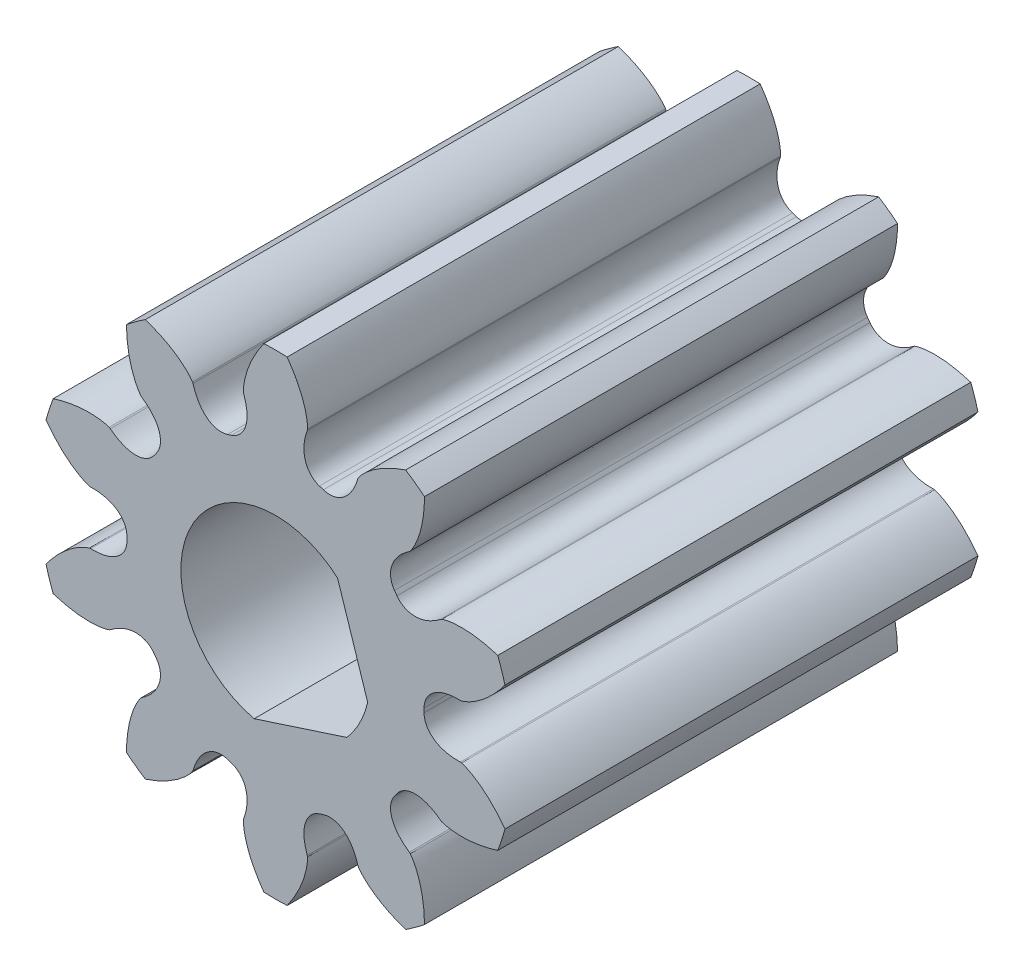
SolidWorks part; units mm, degrees
ref_plane "Front Plane" through (0, 0, 0) normal (0, 0, 1) x (1, 0, 0)
ref_plane "Top Plane" through (0, 0, 0) normal (0, 1, 0) x (1, 0, 0)
ref_plane "Right Plane" through (0, 0, 0) normal (1, 0, 0) x (0, 0, -1)
sketch "Sketch1"
  line L0 (2.4361, 14.0981) -> (2.4176, 14.0011)
  line L1 (0, 19.1675) -> (0, 0) construction
  line L2 (0, 0) -> (0, 19.1675) construction
  line L3 (-2.4361, 14.0981) -> (-2.4176, 14.0011)
  arc A0 (-3.3565, 10.8014) -> (3.3565, 10.8014) centre (0, 0) ccw
  spline S0 degree 3 poles (0, 19.1675) (0.4091, 18.718) (0.9503, 18.0334) (1.5253, 17.0907) (1.8433, 16.4657) (2.08, 15.8962) (2.2459, 15.3905) (2.3525, 14.9558) (2.4222, 14.5338) (2.4407, 14.2555) (2.4361, 14.0981) knots 0 0 0 0 0.317754 0.454552 0.576631 0.68399 0.776631 0.854552 0.917754 1 1 1 1
  spline S1 degree 3 poles (2.4176, 14.0011) (2.3326, 13.767) (2.2324, 13.4128) (2.1686, 12.9356) (2.1589, 12.5901) (2.1905, 12.2478) (2.2716, 11.9071) (2.4153, 11.5697) (2.723, 11.126) (3.0809, 10.8855) (3.3565, 10.8014) knots 0 0 0 0 0.200126 0.294348 0.386168 0.477231 0.569745 0.66645 0.770113 1 1 1 1
  spline S2 degree 3 poles (-2.4176, 14.0011) (-2.3326, 13.767) (-2.2324, 13.4128) (-2.1686, 12.9356) (-2.1589, 12.5901) (-2.1905, 12.2478) (-2.2716, 11.9071) (-2.4153, 11.5697) (-2.723, 11.126) (-3.0809, 10.8855) (-3.3565, 10.8014) knots 0 0 0 0 0.200126 0.294348 0.386168 0.477231 0.569745 0.66645 0.770113 1 1 1 1
  spline S3 degree 3 poles (0, 19.1675) (-0.4091, 18.718) (-0.9503, 18.0334) (-1.5253, 17.0907) (-1.8433, 16.4657) (-2.08, 15.8962) (-2.2459, 15.3905) (-2.3525, 14.9558) (-2.4222, 14.5338) (-2.4407, 14.2555) (-2.4361, 14.0981) knots 0 0 0 0 0.317754 0.454552 0.576631 0.68399 0.776631 0.854552 0.917754 1 1 1 1
  point P2 (0, 19.1675)
  point P4 (0.6151, 18.4382)
  point P5 (1.1227, 17.7322)
  point P6 (1.5306, 17.0614)
  point P7 (1.8474, 16.4366)
  point P8 (2.0828, 15.8672)
  point P9 (2.2476, 15.3617)
  point P10 (2.353, 14.9271)
  point P11 (2.4112, 14.5691)
  point P12 (2.4346, 14.2919)
  point P13 (2.4361, 14.0981)
  point P14 (2.4176, 14.0011)
  point P15 (2.3014, 13.6372)
  point P18 (2.2202, 13.281)
  point P19 (2.1744, 12.9321)
  point P20 (2.1658, 12.5893)
  point P21 (2.1982, 12.2508)
  point P22 (2.2795, 11.915)
  point P23 (2.4224, 11.5834)
  point P24 (2.6443, 11.2662)
  point P25 (2.9589, 10.9909)
  point P26 (3.3565, 10.8014)
  dimension "D1" = 0
  dimension "D2" = 0
  dimension "D3" = 0.6151
  dimension "D4" = 1.1227
  dimension "D24" = 0
other "AlignGroup4" parameters "D1"=14.359, "D2"=4.3343, "D3"=15.4996, "D4"=22.2419, "D5"=1.5306, "D6"=1.8474, "D7"=2.0828, "D8"=2.2476, "D9"=2.353, "D10"=2.4112, "D11"=2.4346, "D12"=2.4361, "D13"=2.4176, "D14"=2.3014, "D15"=2.2202, "D16"=2.1744, "D17"=2.1658, "D18"=2.1982, "D19"=2.2795, "D20"=2.4224, "D21"=2.6443, "D22"=2.9589, "D23"=3.3565, "D24"=0, "D25"=19.1675, "D26"=18.4382, "D27"=17.7322, "D28"=17.0614, "D29"=16.4366, "D30"=15.8672, "D31"=15.3617, "D32"=14.9271, "D33"=14.5691, "D34"=14.2919, "D35"=14.0981, "D36"=14.0011, "D37"=13.6372, "D38"=13.281, "D39"=12.9321, "D40"=12.5893, "D41"=12.2508, "D42"=11.915, "D43"=11.5834, "D44"=11.2662, "D45"=10.9909, "D46"=10.8014
other "AlignGroup5"
extrude "Tooth" add sketch "Sketch1" along normal blind 36
pattern_circular "Teeth" count 10 over 360 about axis through (0, 0, 36) along (0, 0, -1) of "Tooth"
sketch "Sketch6" plane through (0, 0, 0) normal (0, 0, 1) x (1, 0, 0)
  circle A0 centre (0, 0) radius 18.0975
  dimension "D1" = 36.195
extrude "Addendum" cut sketch "Sketch6" along normal through all flip side to cut
sketch "Sketch7" plane through (0, 0, 36) normal (0, 0, 1) x (1, 0, 0)
  line L0 (-1.62, -7.0154) -> (5.4341, -4.7234)
  line L1 (0, 0) -> (3.4953, -10.7573) construction
  line L2 (4.7234, 5.4341) -> (7.0154, -1.62)
  arc A0 (5.4341, -4.7234) -> (7.0154, -1.62) centre (0, 0) ccw
  arc A1 (3.3438, -10.8054) -> (3.6461, -10.7072) centre (0, 0) ccw construction
  arc A2 (4.7234, 5.4341) -> (-1.62, -7.0154) centre (0, 0) ccw
  dimension "D1" = 14.4
  dimension "D2" = 13.3714
  dimension "D3" = 4.1109
  dimension "D4" = 13.3714
extrude "Cut-Extrude4" cut sketch "Sketch7" against normal blind 25
sketch "Sketch8" plane through (1.9071, -5.8694, 0) normal (-0.309, 0.9511, 0) x (0.9511, 0.309, 0)
  line L0 (0, -11) -> (0, -36) construction
  line L4 (-3.7086, -36) -> (3.7086, -36)
  line L5 (3.7086, -36) -> (3.7086, -11)
  line L6 (3.7086, -11) -> (-3.7086, -11)
  line L7 (-3.7086, -11) -> (-3.7086, -36)
  line L8 (-3.7086, -36) -> (3.7086, -36) construction
  line L9 (3.7086, -36) -> (3.7086, -11) construction
  line L10 (3.7086, -11) -> (-3.7086, -11) construction
  line L11 (-3.7086, -11) -> (-3.7086, -36) construction
  circle A0 centre (0, -23.5) radius 1.5
  point P10 (0, -23.5)
  dimension "D2" = 3
  dimension "D1" = 0
extrude "Cut-Extrude5" cut sketch "Sketch8" against normal through all
sketch "Sketch9" plane through (0, 0, 0) normal (0, 0, -1) x (-1, 0, 0)
  line L20 (14.1609, -2.0397) -> (14.0629, -2.0273)
  line L21 (14.0629, 2.0273) -> (14.1609, 2.0397)
  line L22 (12.6553, 6.6734) -> (12.5688, 6.6258)
  line L23 (10.1855, 9.9061) -> (10.2575, 9.9737)
  line L24 (6.3158, 12.8375) -> (6.2738, 12.7481)
  line L25 (2.4176, 14.0011) -> (2.4361, 14.0981)
  line L26 (-2.4361, 14.0981) -> (-2.4176, 14.0011)
  line L27 (-6.2738, 12.7481) -> (-6.3158, 12.8375)
  line L28 (-10.2575, 9.9737) -> (-10.1855, 9.9061)
  line L29 (-12.5688, 6.6258) -> (-12.6553, 6.6734)
  line L30 (-14.1609, 2.0397) -> (-14.0629, 2.0273)
  line L31 (-14.0629, -2.0273) -> (-14.1609, -2.0397)
  line L32 (-12.6553, -6.6734) -> (-12.5688, -6.6258)
  line L33 (-10.1855, -9.9061) -> (-10.2575, -9.9737)
  line L34 (-6.3158, -12.8375) -> (-6.2738, -12.7481)
  line L35 (-2.4176, -14.0011) -> (-2.4361, -14.0981)
  line L36 (2.4361, -14.0981) -> (2.4176, -14.0011)
  line L37 (6.2738, -12.7481) -> (6.3158, -12.8375)
  line L38 (10.2575, -9.9737) -> (10.1855, -9.9061)
  line L39 (12.5688, -6.6258) -> (12.6553, -6.6734)
  line L40 (14.1609, -2.0397) -> (14.0629, -2.0273)
  line L41 (14.0629, 2.0273) -> (14.1609, 2.0397)
  line L42 (12.6553, 6.6734) -> (12.5688, 6.6258)
  line L43 (10.1855, 9.9061) -> (10.2575, 9.9737)
  line L44 (6.3158, 12.8375) -> (6.2738, 12.7481)
  line L45 (2.4176, 14.0011) -> (2.4361, 14.0981)
  line L46 (-2.4361, 14.0981) -> (-2.4176, 14.0011)
  line L47 (-6.2738, 12.7481) -> (-6.3158, 12.8375)
  line L48 (-10.2575, 9.9737) -> (-10.1855, 9.9061)
  line L49 (-12.5688, 6.6258) -> (-12.6553, 6.6734)
  line L50 (-14.1609, 2.0397) -> (-14.0629, 2.0273)
  line L51 (-14.0629, -2.0273) -> (-14.1609, -2.0397)
  line L52 (-12.6553, -6.6734) -> (-12.5688, -6.6258)
  line L53 (-10.1855, -9.9061) -> (-10.2575, -9.9737)
  line L54 (-6.3158, -12.8375) -> (-6.2738, -12.7481)
  line L55 (-2.4176, -14.0011) -> (-2.4361, -14.0981)
  line L56 (2.4361, -14.0981) -> (2.4176, -14.0011)
  line L57 (6.2738, -12.7481) -> (6.3158, -12.8375)
  line L58 (10.2575, -9.9737) -> (10.1855, -9.9061)
  line L59 (12.5688, -6.6258) -> (12.6553, -6.6734)
  arc A20 (16.9173, -6.4284) -> (17.4649, -4.7431) centre (0, 0) ccw
  arc A21 (11.3098, -0.1589) -> (11.3098, 0.1589) centre (0, 0) ccw
  arc A22 (17.4649, 4.7431) -> (16.9173, 6.4284) centre (0, 0) ccw
  arc A23 (9.2433, 6.5192) -> (9.0564, 6.7763) centre (0, 0) ccw
  arc A24 (11.3415, 14.1028) -> (9.9079, 15.1444) centre (0, 0) ccw
  arc A25 (3.6461, 10.7072) -> (3.3438, 10.8054) centre (0, 0) ccw
  arc A26 (0.886, 18.0758) -> (-0.886, 18.0758) centre (0, 0) ccw
  arc A27 (-3.3438, 10.8054) -> (-3.6461, 10.7072) centre (0, 0) ccw
  arc A28 (-9.9079, 15.1444) -> (-11.3415, 14.1028) centre (0, 0) ccw
  arc A29 (-9.0564, 6.7763) -> (-9.2433, 6.5192) centre (0, 0) ccw
  arc A30 (-16.9173, 6.4284) -> (-17.4649, 4.7431) centre (0, 0) ccw
  arc A31 (-11.3098, 0.1589) -> (-11.3098, -0.1589) centre (0, 0) ccw
  arc A32 (-17.4649, -4.7431) -> (-16.9173, -6.4284) centre (0, 0) ccw
  arc A33 (-9.2433, -6.5192) -> (-9.0564, -6.7763) centre (0, 0) ccw
  arc A34 (-11.3415, -14.1028) -> (-9.9079, -15.1444) centre (0, 0) ccw
  arc A35 (-3.6461, -10.7072) -> (-3.3438, -10.8054) centre (0, 0) ccw
  arc A36 (-0.886, -18.0758) -> (0.886, -18.0758) centre (0, 0) ccw
  arc A37 (3.3438, -10.8054) -> (3.6461, -10.7072) centre (0, 0) ccw
  arc A38 (9.9079, -15.1444) -> (11.3415, -14.1028) centre (0, 0) ccw
  arc A39 (9.0564, -6.7763) -> (9.2433, -6.5192) centre (0, 0) ccw
  arc A40 (16.9173, -6.4284) -> (17.4649, -4.7431) centre (0, 0) ccw
  arc A41 (11.3098, -0.1589) -> (11.3098, 0.1589) centre (0, 0) ccw
  arc A42 (17.4649, 4.7431) -> (16.9173, 6.4284) centre (0, 0) ccw
  arc A43 (9.2433, 6.5192) -> (9.0564, 6.7763) centre (0, 0) ccw
  arc A44 (11.3415, 14.1028) -> (9.9079, 15.1444) centre (0, 0) ccw
  arc A45 (3.6461, 10.7072) -> (3.3438, 10.8054) centre (0, 0) ccw
  arc A46 (0.886, 18.0758) -> (-0.886, 18.0758) centre (0, 0) ccw
  arc A47 (-3.3438, 10.8054) -> (-3.6461, 10.7072) centre (0, 0) ccw
  arc A48 (-9.9079, 15.1444) -> (-11.3415, 14.1028) centre (0, 0) ccw
  arc A49 (-9.0564, 6.7763) -> (-9.2433, 6.5192) centre (0, 0) ccw
  arc A50 (-16.9173, 6.4284) -> (-17.4649, 4.7431) centre (0, 0) ccw
  arc A51 (-11.3098, 0.1589) -> (-11.3098, -0.1589) centre (0, 0) ccw
  arc A52 (-17.4649, -4.7431) -> (-16.9173, -6.4284) centre (0, 0) ccw
  arc A53 (-9.2433, -6.5192) -> (-9.0564, -6.7763) centre (0, 0) ccw
  arc A54 (-11.3415, -14.1028) -> (-9.9079, -15.1444) centre (0, 0) ccw
  arc A55 (-3.6461, -10.7072) -> (-3.3438, -10.8054) centre (0, 0) ccw
  arc A56 (-0.886, -18.0758) -> (0.886, -18.0758) centre (0, 0) ccw
  arc A57 (3.3438, -10.8054) -> (3.6461, -10.7072) centre (0, 0) ccw
  arc A58 (9.9079, -15.1444) -> (11.3415, -14.1028) centre (0, 0) ccw
  arc A59 (9.0564, -6.7763) -> (9.2433, -6.5192) centre (0, 0) ccw
  spline S40 degree 3 poles (522.5428, 2951.3914) (-112.6678, -210.8006) (43.5083, -35.0589) (16.7256, -3.8307) (16.2294, -3.3351) (15.7609, -2.934) (15.3313, -2.62) (14.9507, -2.3842) (4.0763, 3.2477) (-28.6818, -37.3785) (-500.9762, -2956.8331) knots -21.152861 -21.152861 -21.152861 -21.152861 0.07269 0.209488 0.331567 0.438926 0.531567 0.609488 0.67269 6.927682 6.927682 6.927682 6.927682 only from (17.4649, -4.7431) to (14.1609, -2.0397)
  spline S41 degree 3 poles (-1882.5898, -2326.0124) (70.5572, 137.468) (32.2563, -5.4661) (12.9726, -1.9349) (12.641, -1.8374) (12.3253, -1.7014) (12.0263, -1.519) (11.7499, -1.2781) (4.3858, 8.4005) (109.0954, 85.4158) (1889.5302, -2336.0275) knots -15.333647 -15.333647 -15.333647 -15.333647 0.20368 0.297902 0.389722 0.480785 0.573299 0.670004 0.773667 10.262957 10.262957 10.262957 10.262957 only from (14.0629, -2.0273) to (11.3098, -0.1589)
  spline S42 degree 3 poles (1889.5208, 2336.0147) (109.095, -85.4156) (4.3859, -8.4005) (11.7499, 1.2781) (12.0263, 1.519) (12.3253, 1.7014) (12.641, 1.8374) (12.9726, 1.9349) (32.2563, 5.4662) (70.5573, -137.4686) (-1882.6014, 2326.027) knots -9.26294 -9.26294 -9.26294 -9.26294 0.226333 0.329996 0.426701 0.519215 0.610278 0.702098 0.79632 16.333677 16.333677 16.333677 16.333677 only from (11.3098, 0.1589) to (14.0629, 2.0273)
  spline S43 degree 3 poles (-500.9951, 2956.9497) (-28.6827, 37.3796) (4.0761, -3.2478) (14.9507, 2.3842) (15.3313, 2.62) (15.7609, 2.934) (16.2294, 3.3351) (16.7256, 3.8307) (43.5082, 35.0587) (-112.6664, 210.799) (522.5344, -2951.3495) knots -5.927765 -5.927765 -5.927765 -5.927765 0.32731 0.390512 0.468433 0.561074 0.668433 0.790512 0.92731 22.152768 22.152768 22.152768 22.152768 only from (14.1609, 2.0397) to (17.4649, 4.7431)
  spline S44 degree 3 poles (-1312.0383, 2694.8688) (32.7553, -236.7657) (55.8061, -2.7897) (15.7829, 6.7319) (15.0902, 6.8413) (14.4754, 6.8904) (13.9432, 6.8919) (13.4968, 6.8589) (1.3888, 5.0234) (-1.2335, -47.0986) (1332.6846, -2686.5947) knots -21.152861 -21.152861 -21.152861 -21.152861 0.07269 0.209488 0.331567 0.438926 0.531567 0.609488 0.67269 6.927682 6.927682 6.927682 6.927682 only from (16.9173, 6.4284) to (12.6553, 6.6734)
  spline S45 degree 3 poles (-155.8514, -2988.342) (-23.7197, 152.6864) (29.3088, 14.5375) (11.6324, 6.0598) (11.3068, 5.9437) (10.9714, 5.8681) (10.6223, 5.8399) (10.2571, 5.8724) (-1.3895, 9.3741) (38.0539, 133.2275) (2901.7445, -779.248) knots -15.333647 -15.333647 -15.333647 -15.333647 0.20368 0.297902 0.389722 0.480785 0.573299 0.670004 0.773667 10.262957 10.262957 10.262957 10.262957 only from (12.5688, 6.6258) to (9.2433, 6.5192)
  spline S46 degree 3 poles (155.5794, 3000.508) (138.4657, -4.9782) (8.4859, -4.2182) (8.7546, 7.9404) (8.8366, 8.2978) (8.9713, 8.6211) (9.1468, 8.9167) (9.3578, 9.1905) (22.883, 23.382) (137.8841, -69.7418) (-2890.2609, 775.23) knots -9.26294 -9.26294 -9.26294 -9.26294 0.226333 0.329996 0.426701 0.519215 0.610278 0.702098 0.79632 16.333677 16.333677 16.333677 16.333677 only from (9.0564, 6.7763) to (10.1855, 9.9061)
  spline S47 degree 3 poles (-2143.365, 2097.745) (-45.1759, 13.3815) (5.2067, -0.2316) (10.694, 10.7167) (10.8633, 11.1311) (11.0263, 11.6377) (11.1696, 12.2376) (11.2796, 12.9301) (14.5919, 53.9366) (-215.0536, 104.3164) (2157.4989, -2080.5539) knots -5.927765 -5.927765 -5.927765 -5.927765 0.32731 0.390512 0.468433 0.561074 0.668433 0.790512 0.92731 22.152768 22.152768 22.152768 22.152768 only from (10.2575, 9.9737) to (11.3415, 14.1028)
  spline S48 degree 3 poles (-2645.4654, 1408.9979) (165.667, -172.2944) (46.7878, 30.5451) (8.8117, 14.7232) (8.187, 14.4045) (7.6608, 14.0829) (7.2294, 13.7713) (6.8876, 13.4822) (-1.8291, 4.8804) (26.6859, -38.8286) (2657.3052, -1390.1684) knots -21.152861 -21.152861 -21.152861 -21.152861 0.07269 0.209488 0.331567 0.438926 0.531567 0.609488 0.67269 6.927682 6.927682 6.927682 6.927682 only from (9.9079, 15.1444) to (6.3158, 12.8375)
  spline S49 degree 3 poles (1630.417, -2509.2266) (-108.9365, 109.5838) (15.1663, 28.9884) (5.849, 11.7398) (5.6537, 11.4545) (5.4269, 11.1962) (5.161, 10.9682) (4.8465, 10.7798) (-6.6341, 6.7671) (-47.523, 130.1508) (2805.5911, 1075.1778) knots -15.333647 -15.333647 -15.333647 -15.333647 0.20368 0.297902 0.389722 0.480785 0.573299 0.670004 0.773667 10.262957 10.262957 10.262957 10.262957 only from (6.2738, 12.7481) to (3.6461, 10.7072)
  spline S50 degree 3 poles (-1637.788, 2518.9093) (114.9472, 77.3607) (9.3447, 1.5753) (2.4153, 11.5697) (2.2716, 11.9071) (2.1905, 12.2478) (2.1589, 12.5901) (2.1686, 12.9356) (4.7691, 32.3667) (152.5438, 24.6239) (-2793.939, -1071.6785) knots -9.26294 -9.26294 -9.26294 -9.26294 0.226333 0.329996 0.426701 0.519215 0.610278 0.702098 0.79632 16.333677 16.333677 16.333677 16.333677 only from (3.3438, 10.8054) to (2.4176, 14.0011)
  spline S51 degree 3 poles (-2967.0423, 437.2731) (-44.4135, -15.7279) (4.3484, 2.873) (2.3525, 14.9558) (2.2459, 15.3905) (2.08, 15.8962) (1.8433, 16.4657) (1.5253, 17.0907) (-19.8981, 52.2125) (-235.2976, -42.0116) (2968.3722, -415.0574) knots -5.927765 -5.927765 -5.927765 -5.927765 0.32731 0.390512 0.468433 0.561074 0.668433 0.790512 0.92731 22.152768 22.152768 22.152768 22.152768 only from (2.4361, 14.0981) to (0.886, 18.0758)
  spline S52 degree 3 poles (-2968.4147, -415.0623) (235.2995, -42.0125) (19.8981, 52.2127) (-1.5253, 17.0907) (-1.8433, 16.4657) (-2.08, 15.8962) (-2.2459, 15.3905) (-2.3525, 14.9558) (-4.3484, 2.8732) (44.4122, -15.7274) (2966.9256, 437.255) knots -21.152861 -21.152861 -21.152861 -21.152861 0.07269 0.209488 0.331567 0.438926 0.531567 0.609488 0.67269 6.927682 6.927682 6.927682 6.927682 only from (-0.886, 18.0758) to (-2.4361, 14.0981)
  spline S53 degree 3 poles (2793.9215, -1071.6719) (-152.5432, 24.6239) (-4.7691, 32.3667) (-2.1686, 12.9356) (-2.1589, 12.5901) (-2.1905, 12.2478) (-2.2716, 11.9071) (-2.4153, 11.5697) (-9.3447, 1.5753) (-114.9476, 77.3609) (1637.7972, 2518.9222) knots -15.333647 -15.333647 -15.333647 -15.333647 0.20368 0.297902 0.389722 0.480785 0.573299 0.670004 0.773667 10.262957 10.262957 10.262957 10.262957 only from (-2.4176, 14.0011) to (-3.3438, 10.8054)
  spline S54 degree 3 poles (-2805.576, 1075.1728) (47.5228, 130.1504) (6.6341, 6.7671) (-4.8465, 10.7798) (-5.161, 10.9682) (-5.4269, 11.1962) (-5.6537, 11.4545) (-5.849, 11.7398) (-15.1664, 28.9884) (108.937, 109.5841) (-1630.4273, -2509.2422) knots -9.26294 -9.26294 -9.26294 -9.26294 0.226333 0.329996 0.426701 0.519215 0.610278 0.702098 0.79632 16.333677 16.333677 16.333677 16.333677 only from (-3.6461, 10.7072) to (-6.2738, 12.7481)
  spline S55 degree 3 poles (-2657.4103, -1390.2224) (-26.6867, -38.8298) (1.8292, 4.8803) (-6.8876, 13.4822) (-7.2294, 13.7713) (-7.6608, 14.0829) (-8.187, 14.4045) (-8.8117, 14.7232) (-46.7876, 30.545) (-165.666, -172.2926) (2645.4282, 1408.9769) knots -5.927765 -5.927765 -5.927765 -5.927765 0.32731 0.390512 0.468433 0.561074 0.668433 0.790512 0.92731 22.152768 22.152768 22.152768 22.152768 only from (-6.3158, 12.8375) to (-9.9079, 15.1444)
  spline S56 degree 3 poles (-2157.5304, -2080.5828) (215.0556, 104.3168) (-14.5919, 53.9368) (-11.2796, 12.9301) (-11.1696, 12.2376) (-11.0263, 11.6377) (-10.8633, 11.1311) (-10.694, 10.7167) (-5.2067, -0.2315) (45.1746, 13.3811) (2143.2812, 2097.6618) knots -21.152861 -21.152861 -21.152861 -21.152861 0.07269 0.209488 0.331567 0.438926 0.531567 0.609488 0.67269 6.927682 6.927682 6.927682 6.927682 only from (-11.3415, 14.1028) to (-10.2575, 9.9737)
  spline S57 degree 3 poles (2890.2429, 775.225) (-137.8836, -69.7415) (-22.8829, 23.382) (-9.3578, 9.1905) (-9.1468, 8.9167) (-8.9713, 8.6211) (-8.8366, 8.2978) (-8.7546, 7.9404) (-8.4859, -4.2182) (-138.4662, -4.9782) (-155.5795, 3000.5239) knots -15.333647 -15.333647 -15.333647 -15.333647 0.20368 0.297902 0.389722 0.480785 0.573299 0.670004 0.773667 10.262957 10.262957 10.262957 10.262957 only from (-10.1855, 9.9061) to (-9.0564, 6.7763)
  spline S58 degree 3 poles (-2901.7294, -779.2431) (-38.0537, 133.2271) (1.3895, 9.3741) (-10.2571, 5.8724) (-10.6223, 5.8399) (-10.9714, 5.8681) (-11.3068, 5.9437) (-11.6324, 6.0598) (-29.3088, 14.5376) (23.7199, 152.687) (155.8522, -2988.3608) knots -9.26294 -9.26294 -9.26294 -9.26294 0.226333 0.329996 0.426701 0.519215 0.610278 0.702098 0.79632 16.333677 16.333677 16.333677 16.333677 only from (-9.2433, 6.5192) to (-12.5688, 6.6258)
  spline S59 degree 3 poles (-1332.7379, -2686.7001) (1.2336, -47.1) (-1.3887, 5.0234) (-13.4968, 6.8589) (-13.9432, 6.8919) (-14.4754, 6.8904) (-15.0902, 6.8413) (-15.7829, 6.7319) (-55.8059, -2.7896) (-32.7555, -236.7637) (1312.0205, 2694.8299) knots -5.927765 -5.927765 -5.927765 -5.927765 0.32731 0.390512 0.468433 0.561074 0.668433 0.790512 0.92731 22.152768 22.152768 22.152768 22.152768 only from (-12.6553, 6.6734) to (-16.9173, 6.4284)
  spline S60 degree 3 poles (-522.5428, -2951.3914) (112.6678, 210.8006) (-43.5083, 35.0589) (-16.7256, 3.8307) (-16.2294, 3.3351) (-15.7609, 2.934) (-15.3313, 2.62) (-14.9507, 2.3842) (-4.0763, -3.2477) (28.6818, 37.3785) (500.9762, 2956.8331) knots -21.152861 -21.152861 -21.152861 -21.152861 0.07269 0.209488 0.331567 0.438926 0.531567 0.609488 0.67269 6.927682 6.927682 6.927682 6.927682 only from (-17.4649, 4.7431) to (-14.1609, 2.0397)
  spline S61 degree 3 poles (1882.5898, 2326.0124) (-70.5572, -137.468) (-32.2563, 5.4661) (-12.9726, 1.9349) (-12.641, 1.8374) (-12.3253, 1.7014) (-12.0263, 1.519) (-11.7499, 1.2781) (-4.3858, -8.4005) (-109.0954, -85.4158) (-1889.5302, 2336.0275) knots -15.333647 -15.333647 -15.333647 -15.333647 0.20368 0.297902 0.389722 0.480785 0.573299 0.670004 0.773667 10.262957 10.262957 10.262957 10.262957 only from (-14.0629, 2.0273) to (-11.3098, 0.1589)
  spline S62 degree 3 poles (-1889.5208, -2336.0147) (-109.095, 85.4156) (-4.3859, 8.4005) (-11.7499, -1.2781) (-12.0263, -1.519) (-12.3253, -1.7014) (-12.641, -1.8374) (-12.9726, -1.9349) (-32.2563, -5.4662) (-70.5573, 137.4686) (1882.6014, -2326.027) knots -9.26294 -9.26294 -9.26294 -9.26294 0.226333 0.329996 0.426701 0.519215 0.610278 0.702098 0.79632 16.333677 16.333677 16.333677 16.333677 only from (-11.3098, -0.1589) to (-14.0629, -2.0273)
  spline S63 degree 3 poles (500.9951, -2956.9497) (28.6827, -37.3796) (-4.0761, 3.2478) (-14.9507, -2.3842) (-15.3313, -2.62) (-15.7609, -2.934) (-16.2294, -3.3351) (-16.7256, -3.8307) (-43.5082, -35.0587) (112.6664, -210.799) (-522.5344, 2951.3495) knots -5.927765 -5.927765 -5.927765 -5.927765 0.32731 0.390512 0.468433 0.561074 0.668433 0.790512 0.92731 22.152768 22.152768 22.152768 22.152768 only from (-14.1609, -2.0397) to (-17.4649, -4.7431)
  spline S64 degree 3 poles (1312.0383, -2694.8688) (-32.7553, 236.7657) (-55.8061, 2.7897) (-15.7829, -6.7319) (-15.0902, -6.8413) (-14.4754, -6.8904) (-13.9432, -6.8919) (-13.4968, -6.8589) (-1.3888, -5.0234) (1.2335, 47.0986) (-1332.6846, 2686.5947) knots -21.152861 -21.152861 -21.152861 -21.152861 0.07269 0.209488 0.331567 0.438926 0.531567 0.609488 0.67269 6.927682 6.927682 6.927682 6.927682 only from (-16.9173, -6.4284) to (-12.6553, -6.6734)
  spline S65 degree 3 poles (155.8514, 2988.342) (23.7197, -152.6864) (-29.3088, -14.5375) (-11.6324, -6.0598) (-11.3068, -5.9437) (-10.9714, -5.8681) (-10.6223, -5.8399) (-10.2571, -5.8724) (1.3895, -9.3741) (-38.0539, -133.2275) (-2901.7445, 779.248) knots -15.333647 -15.333647 -15.333647 -15.333647 0.20368 0.297902 0.389722 0.480785 0.573299 0.670004 0.773667 10.262957 10.262957 10.262957 10.262957 only from (-12.5688, -6.6258) to (-9.2433, -6.5192)
  spline S66 degree 3 poles (-155.5794, -3000.508) (-138.4657, 4.9782) (-8.4859, 4.2182) (-8.7546, -7.9404) (-8.8366, -8.2978) (-8.9713, -8.6211) (-9.1468, -8.9167) (-9.3578, -9.1905) (-22.883, -23.382) (-137.8841, 69.7418) (2890.2609, -775.23) knots -9.26294 -9.26294 -9.26294 -9.26294 0.226333 0.329996 0.426701 0.519215 0.610278 0.702098 0.79632 16.333677 16.333677 16.333677 16.333677 only from (-9.0564, -6.7763) to (-10.1855, -9.9061)
  spline S67 degree 3 poles (2143.365, -2097.745) (45.1759, -13.3815) (-5.2067, 0.2316) (-10.694, -10.7167) (-10.8633, -11.1311) (-11.0263, -11.6377) (-11.1696, -12.2376) (-11.2796, -12.9301) (-14.5919, -53.9366) (215.0536, -104.3164) (-2157.4989, 2080.5539) knots -5.927765 -5.927765 -5.927765 -5.927765 0.32731 0.390512 0.468433 0.561074 0.668433 0.790512 0.92731 22.152768 22.152768 22.152768 22.152768 only from (-10.2575, -9.9737) to (-11.3415, -14.1028)
  spline S68 degree 3 poles (2645.4654, -1408.9979) (-165.667, 172.2944) (-46.7878, -30.5451) (-8.8117, -14.7232) (-8.187, -14.4045) (-7.6608, -14.0829) (-7.2294, -13.7713) (-6.8876, -13.4822) (1.8291, -4.8804) (-26.6859, 38.8286) (-2657.3052, 1390.1684) knots -21.152861 -21.152861 -21.152861 -21.152861 0.07269 0.209488 0.331567 0.438926 0.531567 0.609488 0.67269 6.927682 6.927682 6.927682 6.927682 only from (-9.9079, -15.1444) to (-6.3158, -12.8375)
  spline S69 degree 3 poles (-1630.417, 2509.2266) (108.9365, -109.5838) (-15.1663, -28.9884) (-5.849, -11.7398) (-5.6537, -11.4545) (-5.4269, -11.1962) (-5.161, -10.9682) (-4.8465, -10.7798) (6.6341, -6.7671) (47.523, -130.1508) (-2805.5911, -1075.1778) knots -15.333647 -15.333647 -15.333647 -15.333647 0.20368 0.297902 0.389722 0.480785 0.573299 0.670004 0.773667 10.262957 10.262957 10.262957 10.262957 only from (-6.2738, -12.7481) to (-3.6461, -10.7072)
  spline S70 degree 3 poles (1637.788, -2518.9093) (-114.9472, -77.3607) (-9.3447, -1.5753) (-2.4153, -11.5697) (-2.2716, -11.9071) (-2.1905, -12.2478) (-2.1589, -12.5901) (-2.1686, -12.9356) (-4.7691, -32.3667) (-152.5438, -24.6239) (2793.939, 1071.6785) knots -9.26294 -9.26294 -9.26294 -9.26294 0.226333 0.329996 0.426701 0.519215 0.610278 0.702098 0.79632 16.333677 16.333677 16.333677 16.333677 only from (-3.3438, -10.8054) to (-2.4176, -14.0011)
  spline S71 degree 3 poles (2967.0423, -437.2731) (44.4135, 15.7279) (-4.3484, -2.873) (-2.3525, -14.9558) (-2.2459, -15.3905) (-2.08, -15.8962) (-1.8433, -16.4657) (-1.5253, -17.0907) (19.8981, -52.2125) (235.2976, 42.0116) (-2968.3722, 415.0574) knots -5.927765 -5.927765 -5.927765 -5.927765 0.32731 0.390512 0.468433 0.561074 0.668433 0.790512 0.92731 22.152768 22.152768 22.152768 22.152768 only from (-2.4361, -14.0981) to (-0.886, -18.0758)
  spline S72 degree 3 poles (2968.4147, 415.0623) (-235.2995, 42.0125) (-19.8981, -52.2127) (1.5253, -17.0907) (1.8433, -16.4657) (2.08, -15.8962) (2.2459, -15.3905) (2.3525, -14.9558) (4.3484, -2.8732) (-44.4122, 15.7274) (-2966.9256, -437.255) knots -21.152861 -21.152861 -21.152861 -21.152861 0.07269 0.209488 0.331567 0.438926 0.531567 0.609488 0.67269 6.927682 6.927682 6.927682 6.927682 only from (0.886, -18.0758) to (2.4361, -14.0981)
  spline S73 degree 3 poles (-2793.9215, 1071.6719) (152.5432, -24.6239) (4.7691, -32.3667) (2.1686, -12.9356) (2.1589, -12.5901) (2.1905, -12.2478) (2.2716, -11.9071) (2.4153, -11.5697) (9.3447, -1.5753) (114.9476, -77.3609) (-1637.7972, -2518.9222) knots -15.333647 -15.333647 -15.333647 -15.333647 0.20368 0.297902 0.389722 0.480785 0.573299 0.670004 0.773667 10.262957 10.262957 10.262957 10.262957 only from (2.4176, -14.0011) to (3.3438, -10.8054)
  spline S74 degree 3 poles (2805.576, -1075.1728) (-47.5228, -130.1504) (-6.6341, -6.7671) (4.8465, -10.7798) (5.161, -10.9682) (5.4269, -11.1962) (5.6537, -11.4545) (5.849, -11.7398) (15.1664, -28.9884) (-108.937, -109.5841) (1630.4273, 2509.2422) knots -9.26294 -9.26294 -9.26294 -9.26294 0.226333 0.329996 0.426701 0.519215 0.610278 0.702098 0.79632 16.333677 16.333677 16.333677 16.333677 only from (3.6461, -10.7072) to (6.2738, -12.7481)
  spline S75 degree 3 poles (2657.4103, 1390.2224) (26.6867, 38.8298) (-1.8292, -4.8803) (6.8876, -13.4822) (7.2294, -13.7713) (7.6608, -14.0829) (8.187, -14.4045) (8.8117, -14.7232) (46.7876, -30.545) (165.666, 172.2926) (-2645.4282, -1408.9769) knots -5.927765 -5.927765 -5.927765 -5.927765 0.32731 0.390512 0.468433 0.561074 0.668433 0.790512 0.92731 22.152768 22.152768 22.152768 22.152768 only from (6.3158, -12.8375) to (9.9079, -15.1444)
  spline S76 degree 3 poles (2157.5304, 2080.5828) (-215.0556, -104.3168) (14.5919, -53.9368) (11.2796, -12.9301) (11.1696, -12.2376) (11.0263, -11.6377) (10.8633, -11.1311) (10.694, -10.7167) (5.2067, 0.2315) (-45.1746, -13.3811) (-2143.2812, -2097.6618) knots -21.152861 -21.152861 -21.152861 -21.152861 0.07269 0.209488 0.331567 0.438926 0.531567 0.609488 0.67269 6.927682 6.927682 6.927682 6.927682 only from (11.3415, -14.1028) to (10.2575, -9.9737)
  spline S77 degree 3 poles (-2890.2429, -775.225) (137.8836, 69.7415) (22.8829, -23.382) (9.3578, -9.1905) (9.1468, -8.9167) (8.9713, -8.6211) (8.8366, -8.2978) (8.7546, -7.9404) (8.4859, 4.2182) (138.4662, 4.9782) (155.5795, -3000.5239) knots -15.333647 -15.333647 -15.333647 -15.333647 0.20368 0.297902 0.389722 0.480785 0.573299 0.670004 0.773667 10.262957 10.262957 10.262957 10.262957 only from (10.1855, -9.9061) to (9.0564, -6.7763)
  spline S78 degree 3 poles (2901.7294, 779.2431) (38.0537, -133.2271) (-1.3895, -9.3741) (10.2571, -5.8724) (10.6223, -5.8399) (10.9714, -5.8681) (11.3068, -5.9437) (11.6324, -6.0598) (29.3088, -14.5376) (-23.7199, -152.687) (-155.8522, 2988.3608) knots -9.26294 -9.26294 -9.26294 -9.26294 0.226333 0.329996 0.426701 0.519215 0.610278 0.702098 0.79632 16.333677 16.333677 16.333677 16.333677 only from (9.2433, -6.5192) to (12.5688, -6.6258)
  spline S79 degree 3 poles (1332.7379, 2686.7001) (-1.2336, 47.1) (1.3887, -5.0234) (13.4968, -6.8589) (13.9432, -6.8919) (14.4754, -6.8904) (15.0902, -6.8413) (15.7829, -6.7319) (55.8059, 2.7896) (32.7555, 236.7637) (-1312.0205, -2694.8299) knots -5.927765 -5.927765 -5.927765 -5.927765 0.32731 0.390512 0.468433 0.561074 0.668433 0.790512 0.92731 22.152768 22.152768 22.152768 22.152768 only from (12.6553, -6.6734) to (16.9173, -6.4284)
  spline S80 degree 3 poles (17.4649, -4.7431) (17.3825, -4.6311) (17.1389, -4.3127) (16.7256, -3.8307) (16.2294, -3.3351) (15.7609, -2.934) (15.3313, -2.62) (14.9507, -2.3842) (14.571, -2.1876) (14.312, -2.084) (14.1609, -2.0397) knots 0 0 0 0 0.07269 0.209488 0.331567 0.438926 0.531567 0.609488 0.67269 0.754936 0.754936 0.754936 0.754936
  spline S81 degree 3 poles (14.0629, -2.0273) (13.814, -2.0358) (13.4462, -2.0216) (12.9726, -1.9349) (12.641, -1.8374) (12.3253, -1.7014) (12.0263, -1.519) (11.7499, -1.2781) (11.4256, -0.8519) (11.3073, -0.4425) (11.3098, -0.1589) knots 0.003554 0.003554 0.003554 0.003554 0.20368 0.297902 0.389722 0.480785 0.573299 0.670004 0.773667 1 1 1 1
  spline S82 degree 3 poles (11.3098, 0.1589) (11.3073, 0.4425) (11.4256, 0.8519) (11.7499, 1.2781) (12.0263, 1.519) (12.3253, 1.7014) (12.641, 1.8374) (12.9726, 1.9349) (13.4462, 2.0216) (13.814, 2.0358) (14.0629, 2.0273) knots 0 0 0 0 0.226333 0.329996 0.426701 0.519215 0.610278 0.702098 0.79632 0.996446 0.996446 0.996446 0.996446
  spline S83 degree 3 poles (14.1609, 2.0397) (14.312, 2.084) (14.571, 2.1876) (14.9507, 2.3842) (15.3313, 2.62) (15.7609, 2.934) (16.2294, 3.3351) (16.7256, 3.8307) (17.1389, 4.3127) (17.3825, 4.6311) (17.4649, 4.7431) knots 0.245064 0.245064 0.245064 0.245064 0.32731 0.390512 0.468433 0.561074 0.668433 0.790512 0.92731 1 1 1 1
  spline S84 degree 3 poles (16.9173, 6.4284) (16.7848, 6.4705) (16.4006, 6.585) (15.7829, 6.7319) (15.0902, 6.8413) (14.4754, 6.8904) (13.9432, 6.8919) (13.4968, 6.8589) (13.074, 6.7948) (12.8036, 6.7264) (12.6553, 6.6734) knots 0 0 0 0 0.07269 0.209488 0.331567 0.438926 0.531567 0.609488 0.67269 0.754936 0.754936 0.754936 0.754936
  spline S85 degree 3 poles (12.5688, 6.6258) (12.3724, 6.4727) (12.0665, 6.268) (11.6324, 6.0598) (11.3068, 5.9437) (10.9714, 5.8681) (10.6223, 5.8399) (10.2571, 5.8724) (9.7442, 6.0266) (9.4079, 6.2883) (9.2433, 6.5192) knots 0.003554 0.003554 0.003554 0.003554 0.20368 0.297902 0.389722 0.480785 0.573299 0.670004 0.773667 1 1 1 1
  spline S86 degree 3 poles (9.0564, 6.7763) (8.8877, 7.0043) (8.7427, 7.405) (8.7546, 7.9404) (8.8366, 8.2978) (8.9713, 8.6211) (9.1468, 8.9167) (9.3578, 9.1905) (9.69, 9.539) (9.9792, 9.7667) (10.1855, 9.9061) knots 0 0 0 0 0.226333 0.329996 0.426701 0.519215 0.610278 0.702098 0.79632 0.996446 0.996446 0.996446 0.996446
  spline S87 degree 3 poles (10.2575, 9.9737) (10.3537, 10.0984) (10.5023, 10.3344) (10.694, 10.7167) (10.8633, 11.1311) (11.0263, 11.6377) (11.1696, 12.2376) (11.2796, 12.9301) (11.3307, 13.563) (11.3406, 13.9638) (11.3415, 14.1028) knots 0.245064 0.245064 0.245064 0.245064 0.32731 0.390512 0.468433 0.561074 0.668433 0.790512 0.92731 1 1 1 1
  spline S88 degree 3 poles (9.9079, 15.1444) (9.7759, 15.1006) (9.3978, 14.9674) (8.8117, 14.7232) (8.187, 14.4045) (7.6608, 14.0829) (7.2294, 13.7713) (6.8876, 13.4822) (6.5832, 13.1818) (6.4046, 12.9675) (6.3158, 12.8375) knots 0 0 0 0 0.07269 0.209488 0.331567 0.438926 0.531567 0.609488 0.67269 0.754936 0.754936 0.754936 0.754936
  spline S89 degree 3 poles (6.2738, 12.7481) (6.2049, 12.5088) (6.0778, 12.1634) (5.849, 11.7398) (5.6537, 11.4545) (5.4269, 11.1962) (5.161, 10.9682) (4.8465, 10.7798) (4.3409, 10.6031) (3.915, 10.6172) (3.6461, 10.7072) knots 0.003554 0.003554 0.003554 0.003554 0.20368 0.297902 0.389722 0.480785 0.573299 0.670004 0.773667 1 1 1 1
  spline S90 degree 3 poles (3.3438, 10.8054) (3.0733, 10.8906) (2.7205, 11.1296) (2.4153, 11.5697) (2.2716, 11.9071) (2.1905, 12.2478) (2.1589, 12.5901) (2.1686, 12.9356) (2.2324, 13.4128) (2.3326, 13.767) (2.4176, 14.0011) knots 0 0 0 0 0.226333 0.329996 0.426701 0.519215 0.610278 0.702098 0.79632 0.996446 0.996446 0.996446 0.996446
  spline S91 degree 3 poles (2.4361, 14.0981) (2.4407, 14.2555) (2.4222, 14.5338) (2.3525, 14.9558) (2.2459, 15.3905) (2.08, 15.8962) (1.8433, 16.4657) (1.5253, 17.0907) (1.1946, 17.6327) (0.9671, 17.9628) (0.886, 18.0758) knots 0.245064 0.245064 0.245064 0.245064 0.32731 0.390512 0.468433 0.561074 0.668433 0.790512 0.92731 1 1 1 1
  spline S92 degree 3 poles (-0.886, 18.0758) (-0.9671, 17.9628) (-1.1946, 17.6327) (-1.5253, 17.0907) (-1.8433, 16.4657) (-2.08, 15.8962) (-2.2459, 15.3905) (-2.3525, 14.9558) (-2.4222, 14.5338) (-2.4407, 14.2555) (-2.4361, 14.0981) knots 0 0 0 0 0.07269 0.209488 0.331567 0.438926 0.531567 0.609488 0.67269 0.754936 0.754936 0.754936 0.754936
  spline S93 degree 3 poles (-2.4176, 14.0011) (-2.3326, 13.767) (-2.2324, 13.4128) (-2.1686, 12.9356) (-2.1589, 12.5901) (-2.1905, 12.2478) (-2.2716, 11.9071) (-2.4153, 11.5697) (-2.7205, 11.1296) (-3.0733, 10.8906) (-3.3438, 10.8054) knots 0.003554 0.003554 0.003554 0.003554 0.20368 0.297902 0.389722 0.480785 0.573299 0.670004 0.773667 1 1 1 1
  spline S94 degree 3 poles (-3.6461, 10.7072) (-3.915, 10.6172) (-4.3409, 10.6031) (-4.8465, 10.7798) (-5.161, 10.9682) (-5.4269, 11.1962) (-5.6537, 11.4545) (-5.849, 11.7398) (-6.0778, 12.1634) (-6.2049, 12.5088) (-6.2738, 12.7481) knots 0 0 0 0 0.226333 0.329996 0.426701 0.519215 0.610278 0.702098 0.79632 0.996446 0.996446 0.996446 0.996446
  spline S95 degree 3 poles (-6.3158, 12.8375) (-6.4046, 12.9675) (-6.5832, 13.1818) (-6.8876, 13.4822) (-7.2294, 13.7713) (-7.6608, 14.0829) (-8.187, 14.4045) (-8.8117, 14.7232) (-9.3978, 14.9674) (-9.7759, 15.1006) (-9.9079, 15.1444) knots 0.245064 0.245064 0.245064 0.245064 0.32731 0.390512 0.468433 0.561074 0.668433 0.790512 0.92731 1 1 1 1
  spline S96 degree 3 poles (-11.3415, 14.1028) (-11.3406, 13.9638) (-11.3307, 13.563) (-11.2796, 12.9301) (-11.1696, 12.2376) (-11.0263, 11.6377) (-10.8633, 11.1311) (-10.694, 10.7167) (-10.5023, 10.3344) (-10.3537, 10.0984) (-10.2575, 9.9737) knots 0 0 0 0 0.07269 0.209488 0.331567 0.438926 0.531567 0.609488 0.67269 0.754936 0.754936 0.754936 0.754936
  spline S97 degree 3 poles (-10.1855, 9.9061) (-9.9792, 9.7667) (-9.69, 9.539) (-9.3578, 9.1905) (-9.1468, 8.9167) (-8.9713, 8.6211) (-8.8366, 8.2978) (-8.7546, 7.9404) (-8.7427, 7.405) (-8.8877, 7.0043) (-9.0564, 6.7763) knots 0.003554 0.003554 0.003554 0.003554 0.20368 0.297902 0.389722 0.480785 0.573299 0.670004 0.773667 1 1 1 1
  spline S98 degree 3 poles (-9.2433, 6.5192) (-9.4079, 6.2883) (-9.7442, 6.0266) (-10.2571, 5.8724) (-10.6223, 5.8399) (-10.9714, 5.8681) (-11.3068, 5.9437) (-11.6324, 6.0598) (-12.0665, 6.268) (-12.3724, 6.4727) (-12.5688, 6.6258) knots 0 0 0 0 0.226333 0.329996 0.426701 0.519215 0.610278 0.702098 0.79632 0.996446 0.996446 0.996446 0.996446
  spline S99 degree 3 poles (-12.6553, 6.6734) (-12.8036, 6.7264) (-13.074, 6.7948) (-13.4968, 6.8589) (-13.9432, 6.8919) (-14.4754, 6.8904) (-15.0902, 6.8413) (-15.7829, 6.7319) (-16.4006, 6.585) (-16.7848, 6.4705) (-16.9173, 6.4284) knots 0.245064 0.245064 0.245064 0.245064 0.32731 0.390512 0.468433 0.561074 0.668433 0.790512 0.92731 1 1 1 1
  spline S100 degree 3 poles (-17.4649, 4.7431) (-17.3825, 4.6311) (-17.1389, 4.3127) (-16.7256, 3.8307) (-16.2294, 3.3351) (-15.7609, 2.934) (-15.3313, 2.62) (-14.9507, 2.3842) (-14.571, 2.1876) (-14.312, 2.084) (-14.1609, 2.0397) knots 0 0 0 0 0.07269 0.209488 0.331567 0.438926 0.531567 0.609488 0.67269 0.754936 0.754936 0.754936 0.754936
  spline S101 degree 3 poles (-14.0629, 2.0273) (-13.814, 2.0358) (-13.4462, 2.0216) (-12.9726, 1.9349) (-12.641, 1.8374) (-12.3253, 1.7014) (-12.0263, 1.519) (-11.7499, 1.2781) (-11.4256, 0.8519) (-11.3073, 0.4425) (-11.3098, 0.1589) knots 0.003554 0.003554 0.003554 0.003554 0.20368 0.297902 0.389722 0.480785 0.573299 0.670004 0.773667 1 1 1 1
  spline S102 degree 3 poles (-11.3098, -0.1589) (-11.3073, -0.4425) (-11.4256, -0.8519) (-11.7499, -1.2781) (-12.0263, -1.519) (-12.3253, -1.7014) (-12.641, -1.8374) (-12.9726, -1.9349) (-13.4462, -2.0216) (-13.814, -2.0358) (-14.0629, -2.0273) knots 0 0 0 0 0.226333 0.329996 0.426701 0.519215 0.610278 0.702098 0.79632 0.996446 0.996446 0.996446 0.996446
  spline S103 degree 3 poles (-14.1609, -2.0397) (-14.312, -2.084) (-14.571, -2.1876) (-14.9507, -2.3842) (-15.3313, -2.62) (-15.7609, -2.934) (-16.2294, -3.3351) (-16.7256, -3.8307) (-17.1389, -4.3127) (-17.3825, -4.6311) (-17.4649, -4.7431) knots 0.245064 0.245064 0.245064 0.245064 0.32731 0.390512 0.468433 0.561074 0.668433 0.790512 0.92731 1 1 1 1
  spline S104 degree 3 poles (-16.9173, -6.4284) (-16.7848, -6.4705) (-16.4006, -6.585) (-15.7829, -6.7319) (-15.0902, -6.8413) (-14.4754, -6.8904) (-13.9432, -6.8919) (-13.4968, -6.8589) (-13.074, -6.7948) (-12.8036, -6.7264) (-12.6553, -6.6734) knots 0 0 0 0 0.07269 0.209488 0.331567 0.438926 0.531567 0.609488 0.67269 0.754936 0.754936 0.754936 0.754936
  spline S105 degree 3 poles (-12.5688, -6.6258) (-12.3724, -6.4727) (-12.0665, -6.268) (-11.6324, -6.0598) (-11.3068, -5.9437) (-10.9714, -5.8681) (-10.6223, -5.8399) (-10.2571, -5.8724) (-9.7442, -6.0266) (-9.4079, -6.2883) (-9.2433, -6.5192) knots 0.003554 0.003554 0.003554 0.003554 0.20368 0.297902 0.389722 0.480785 0.573299 0.670004 0.773667 1 1 1 1
  spline S106 degree 3 poles (-9.0564, -6.7763) (-8.8877, -7.0043) (-8.7427, -7.405) (-8.7546, -7.9404) (-8.8366, -8.2978) (-8.9713, -8.6211) (-9.1468, -8.9167) (-9.3578, -9.1905) (-9.69, -9.539) (-9.9792, -9.7667) (-10.1855, -9.9061) knots 0 0 0 0 0.226333 0.329996 0.426701 0.519215 0.610278 0.702098 0.79632 0.996446 0.996446 0.996446 0.996446
  spline S107 degree 3 poles (-10.2575, -9.9737) (-10.3537, -10.0984) (-10.5023, -10.3344) (-10.694, -10.7167) (-10.8633, -11.1311) (-11.0263, -11.6377) (-11.1696, -12.2376) (-11.2796, -12.9301) (-11.3307, -13.563) (-11.3406, -13.9638) (-11.3415, -14.1028) knots 0.245064 0.245064 0.245064 0.245064 0.32731 0.390512 0.468433 0.561074 0.668433 0.790512 0.92731 1 1 1 1
  spline S108 degree 3 poles (-9.9079, -15.1444) (-9.7759, -15.1006) (-9.3978, -14.9674) (-8.8117, -14.7232) (-8.187, -14.4045) (-7.6608, -14.0829) (-7.2294, -13.7713) (-6.8876, -13.4822) (-6.5832, -13.1818) (-6.4046, -12.9675) (-6.3158, -12.8375) knots 0 0 0 0 0.07269 0.209488 0.331567 0.438926 0.531567 0.609488 0.67269 0.754936 0.754936 0.754936 0.754936
  spline S109 degree 3 poles (-6.2738, -12.7481) (-6.2049, -12.5088) (-6.0778, -12.1634) (-5.849, -11.7398) (-5.6537, -11.4545) (-5.4269, -11.1962) (-5.161, -10.9682) (-4.8465, -10.7798) (-4.3409, -10.6031) (-3.915, -10.6172) (-3.6461, -10.7072) knots 0.003554 0.003554 0.003554 0.003554 0.20368 0.297902 0.389722 0.480785 0.573299 0.670004 0.773667 1 1 1 1
  spline S110 degree 3 poles (-3.3438, -10.8054) (-3.0733, -10.8906) (-2.7205, -11.1296) (-2.4153, -11.5697) (-2.2716, -11.9071) (-2.1905, -12.2478) (-2.1589, -12.5901) (-2.1686, -12.9356) (-2.2324, -13.4128) (-2.3326, -13.767) (-2.4176, -14.0011) knots 0 0 0 0 0.226333 0.329996 0.426701 0.519215 0.610278 0.702098 0.79632 0.996446 0.996446 0.996446 0.996446
  spline S111 degree 3 poles (-2.4361, -14.0981) (-2.4407, -14.2555) (-2.4222, -14.5338) (-2.3525, -14.9558) (-2.2459, -15.3905) (-2.08, -15.8962) (-1.8433, -16.4657) (-1.5253, -17.0907) (-1.1946, -17.6327) (-0.9671, -17.9628) (-0.886, -18.0758) knots 0.245064 0.245064 0.245064 0.245064 0.32731 0.390512 0.468433 0.561074 0.668433 0.790512 0.92731 1 1 1 1
  spline S112 degree 3 poles (0.886, -18.0758) (0.9671, -17.9628) (1.1946, -17.6327) (1.5253, -17.0907) (1.8433, -16.4657) (2.08, -15.8962) (2.2459, -15.3905) (2.3525, -14.9558) (2.4222, -14.5338) (2.4407, -14.2555) (2.4361, -14.0981) knots 0 0 0 0 0.07269 0.209488 0.331567 0.438926 0.531567 0.609488 0.67269 0.754936 0.754936 0.754936 0.754936
  spline S113 degree 3 poles (2.4176, -14.0011) (2.3326, -13.767) (2.2324, -13.4128) (2.1686, -12.9356) (2.1589, -12.5901) (2.1905, -12.2478) (2.2716, -11.9071) (2.4153, -11.5697) (2.7205, -11.1296) (3.0733, -10.8906) (3.3438, -10.8054) knots 0.003554 0.003554 0.003554 0.003554 0.20368 0.297902 0.389722 0.480785 0.573299 0.670004 0.773667 1 1 1 1
  spline S114 degree 3 poles (3.6461, -10.7072) (3.915, -10.6172) (4.3409, -10.6031) (4.8465, -10.7798) (5.161, -10.9682) (5.4269, -11.1962) (5.6537, -11.4545) (5.849, -11.7398) (6.0778, -12.1634) (6.2049, -12.5088) (6.2738, -12.7481) knots 0 0 0 0 0.226333 0.329996 0.426701 0.519215 0.610278 0.702098 0.79632 0.996446 0.996446 0.996446 0.996446
  spline S115 degree 3 poles (6.3158, -12.8375) (6.4046, -12.9675) (6.5832, -13.1818) (6.8876, -13.4822) (7.2294, -13.7713) (7.6608, -14.0829) (8.187, -14.4045) (8.8117, -14.7232) (9.3978, -14.9674) (9.7759, -15.1006) (9.9079, -15.1444) knots 0.245064 0.245064 0.245064 0.245064 0.32731 0.390512 0.468433 0.561074 0.668433 0.790512 0.92731 1 1 1 1
  spline S116 degree 3 poles (11.3415, -14.1028) (11.3406, -13.9638) (11.3307, -13.563) (11.2796, -12.9301) (11.1696, -12.2376) (11.0263, -11.6377) (10.8633, -11.1311) (10.694, -10.7167) (10.5023, -10.3344) (10.3537, -10.0984) (10.2575, -9.9737) knots 0 0 0 0 0.07269 0.209488 0.331567 0.438926 0.531567 0.609488 0.67269 0.754936 0.754936 0.754936 0.754936
  spline S117 degree 3 poles (10.1855, -9.9061) (9.9792, -9.7667) (9.69, -9.539) (9.3578, -9.1905) (9.1468, -8.9167) (8.9713, -8.6211) (8.8366, -8.2978) (8.7546, -7.9404) (8.7427, -7.405) (8.8877, -7.0043) (9.0564, -6.7763) knots 0.003554 0.003554 0.003554 0.003554 0.20368 0.297902 0.389722 0.480785 0.573299 0.670004 0.773667 1 1 1 1
  spline S118 degree 3 poles (9.2433, -6.5192) (9.4079, -6.2883) (9.7442, -6.0266) (10.2571, -5.8724) (10.6223, -5.8399) (10.9714, -5.8681) (11.3068, -5.9437) (11.6324, -6.0598) (12.0665, -6.268) (12.3724, -6.4727) (12.5688, -6.6258) knots 0 0 0 0 0.226333 0.329996 0.426701 0.519215 0.610278 0.702098 0.79632 0.996446 0.996446 0.996446 0.996446
  spline S119 degree 3 poles (12.6553, -6.6734) (12.8036, -6.7264) (13.074, -6.7948) (13.4968, -6.8589) (13.9432, -6.8919) (14.4754, -6.8904) (15.0902, -6.8413) (15.7829, -6.7319) (16.4006, -6.585) (16.7848, -6.4705) (16.9173, -6.4284) knots 0.245064 0.245064 0.245064 0.245064 0.32731 0.390512 0.468433 0.561074 0.668433 0.790512 0.92731 1 1 1 1
  dimension "D1" = 0
extrude "Cut-Extrude6" [suppressed] cut sketch "Sketch9" against normal offset from surface (28 mm away) 8
equation "\"D2@Sketch7\"=\"D4@Sketch7\""
equation "\"D4@Sketch7\"=\"D1@Sketch7\"*13/14"
